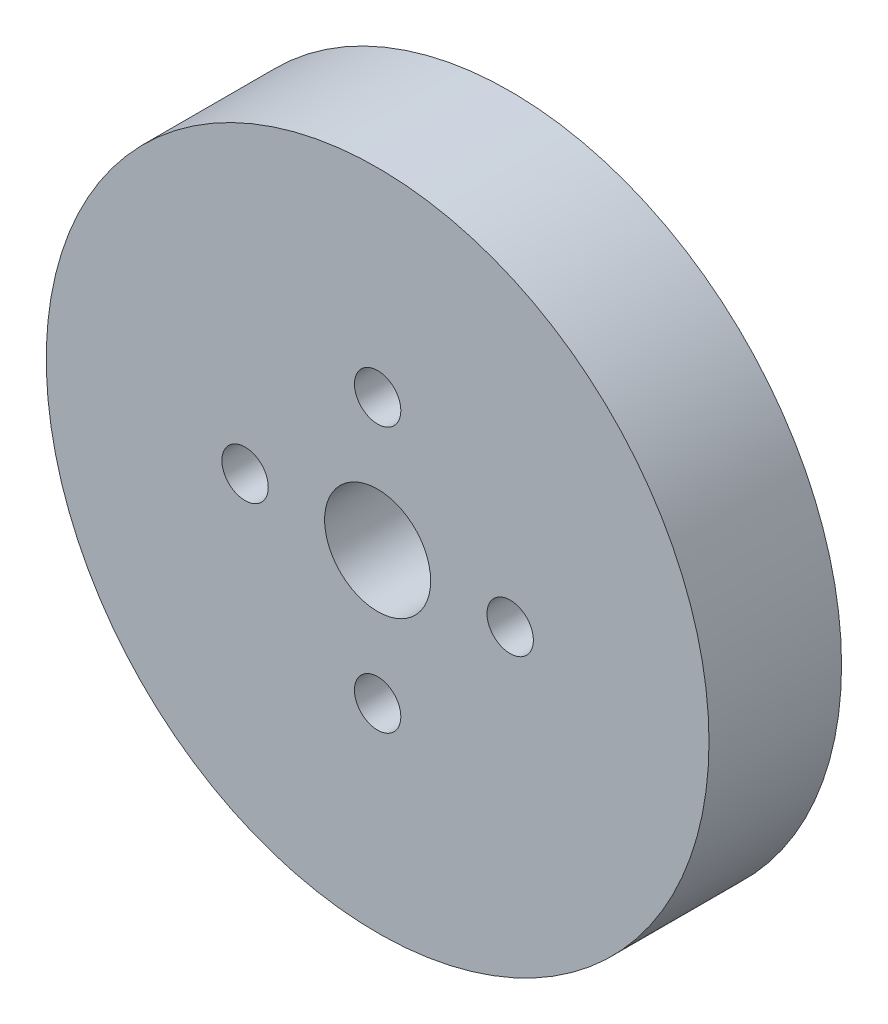
SolidWorks part; units mm, degrees
ref_plane "Front Plane" through (0, 0, 0) normal (0, 0, 1) x (1, 0, 0)
ref_plane "Top Plane" through (0, 0, 0) normal (0, 1, 0) x (1, 0, 0)
ref_plane "Right Plane" through (0, 0, 0) normal (1, 0, 0) x (0, 0, -1)
sketch "Sketch1" plane through (0, 0, 0) normal (0, 0, 1) x (1, 0, 0)
  circle A0 centre (0, 0) radius 25
  dimension "D1" = 50
extrude "Boss-Extrude1" add sketch "Sketch1" along normal blind 10
sketch "Sketch2" plane through (0, 0, 0) normal (0, 0, -1) x (-1, 0, 0)
  circle A0 centre (0, 0) radius 23
  dimension "D1" = 46
extrude "Cut-Extrude1" cut sketch "Sketch2" against normal blind 2
sketch "Sketch3" plane through (0, 0, 10) normal (0, 0, 1) x (1, 0, 0)
  line L0 (0, 0) -> (10, 0) construction
  circle A0 centre (0, 0) radius 4
  circle A1 centre (10, 0) radius 1.75
  circle A2 centre (0, -10) radius 1.75
  circle A3 centre (-10, 0) radius 1.75
  circle A4 centre (0, 10) radius 1.75
  point P14 (0, 0)
  dimension "D1" = 8
  dimension "D2" = 3.5
  dimension "D3" = 10
  dimension "D4" = 4
extrude "Cut-Extrude2" cut sketch "Sketch3" against normal through all
sketch "Sketch4" plane through (0, 0, 2) normal (0, 0, -1) x (-1, 0, 0)
  line L0 (0, 23) -> (0, 18.4645) construction
  line L2 (-0.75, 22.9878) -> (-0.75, 18.4645)
  line L3 (-0.75, 18.4645) -> (0.75, 18.4645)
  line L4 (0.75, 22.9878) -> (0.75, 18.4645)
  line L5 (0, 23) -> (0.75, 18.4645) construction
  line L6 (-0.75, 18.4645) -> (0, 23) construction
  line L7 (0, 18.4645) -> (0, 0) construction
  circle A0 centre (0, 0) radius 23 construction
  circle A1 centre (0, 0) radius 23 construction
  arc A2 (0.75, 22.9878) -> (-0.75, 22.9878) centre (0, 0) ccw
  point P0 (0, 23)
  dimension "D1" = 1.5
  dimension "D2" = 4.5355
extrude "Boss-Extrude2" add sketch "Sketch4" along normal blind 2
pattern_circular "CirPattern1" count 20 over 360 about axis through (0, 0, 0) along (0, 0, 1) of "Boss-Extrude2"
